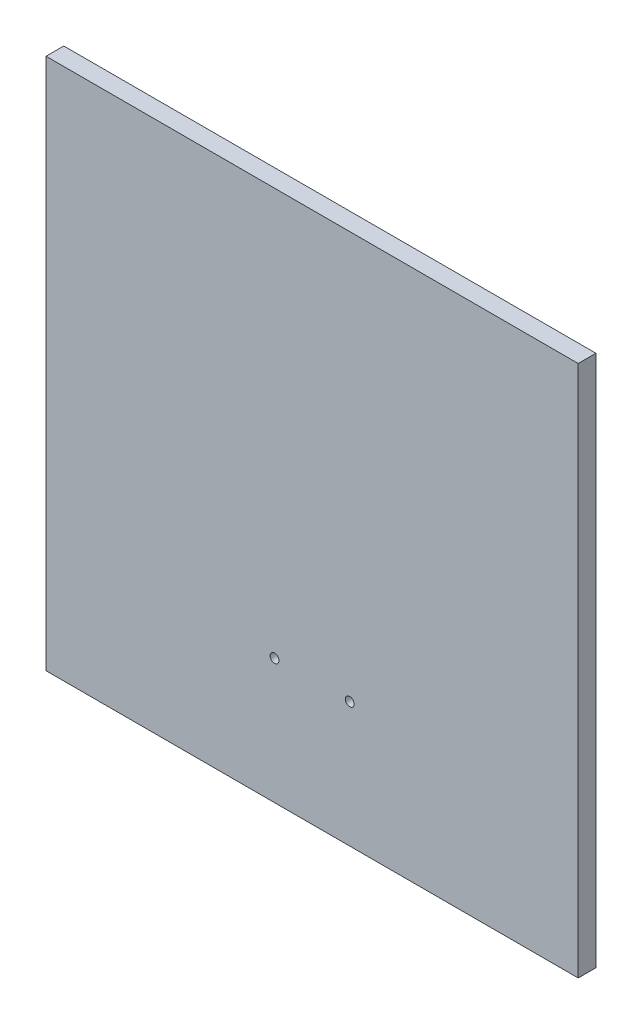
SolidWorks part; units mm, degrees
ref_plane "Front Plane" through (0, 0, 0) normal (0, 0, 1) x (1, 0, 0)
ref_plane "Top Plane" through (0, 0, 0) normal (0, 1, 0) x (1, 0, 0)
ref_plane "Right Plane" through (0, 0, 0) normal (1, 0, 0) x (0, 0, -1)
sketch "Sketch1" plane through (0, 0, 0) normal (0, 0, 1) x (1, 0, 0)
  line L0 (42.4303, -214.5418) -> (42.4303, 85.4582) construction
  line L5 (-107.5697, 85.4582) -> (192.4303, 85.4582)
  line L6 (-107.5697, 85.4582) -> (-107.5697, -214.5418)
  line L7 (-107.5697, -214.5418) -> (192.4303, -214.5418)
  line L8 (192.4303, 85.4582) -> (192.4303, -214.5418)
  line L9 (-107.5697, -151.6415) -> (192.4303, -151.6415) construction
  circle A0 centre (21.2303, -144.0172) radius 2.5
  circle A1 centre (63.6303, -144.0172) radius 2.5
  dimension "D1" = 300
  dimension "D2" = 300
extrude "Boss-Extrude1" add sketch "Sketch1" along normal blind 10
